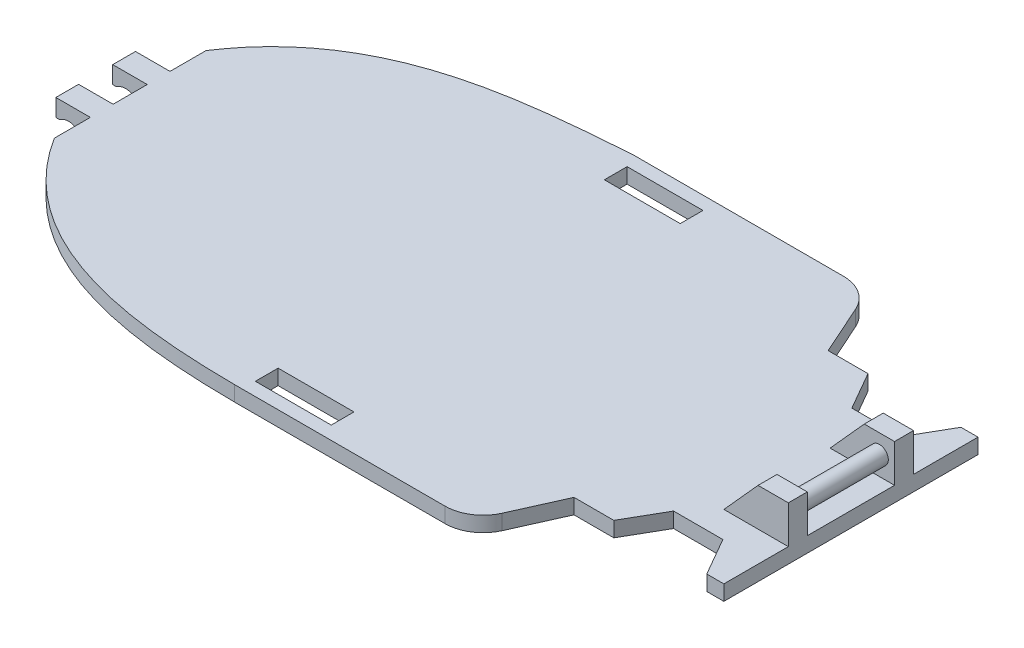
SolidWorks part; units mm, degrees
ref_plane "Front Plane" through (0, 0, 0) normal (0, 0, 1) x (1, 0, 0)
ref_plane "Top Plane" through (0, 0, 0) normal (0, 1, 0) x (1, 0, 0)
ref_plane "Right Plane" through (0, 0, 0) normal (1, 0, 0) x (0, 0, -1)
sketch "Sketch1" plane through (0, 0, 0) normal (0, 1, 0) x (1, 0, 0)
  line L0 (-110, 0) -> (0, 0)
  line L1 (0, 0) -> (0, -105)
  line L2 (0, -105) -> (-110, -105)
  line L4 (-190, -72.5) -> (-190, -32.5)
  spline S0 degree 3 poles (-190, -32.5) (-171.7074, -4.6189) (-138.9899, -2.1787) (-110, 0) knots 0 0 0 0 1 1 1 1
  spline S1 degree 2 poles (-190.0397, -35.2371) (-187.6331, -30.2964) (-183.9056, -25.9107) (-180.479, -21.8792) (-175.9528, -18.3354) (-171.8462, -15.1201) (-166.8566, -12.3231) (-164.564, -11.0379) (-162.0905, -9.8442) (-159.6124, -8.6482) (-157.2765, -7.6915) knots 0 0 0 0.25 0.25 0.5 0.5 0.75 0.75 0.875 0.875 1 1 1 construction
  spline S2 degree 2 poles (-157.2765, -7.6915) (-155.8569, -7.11) (-154.4721, -6.6099) (-153.0466, -6.0951) (-151.6197, -5.6536) (-148.8172, -4.7863) (-145.7427, -4.1123) (-142.8487, -3.4777) (-139.6519, -3.0009) (-136.688, -2.5589) (-133.369, -2.2385) knots 0 0 0 0.125 0.125 0.25 0.25 0.5 0.5 0.75 0.75 1 1 1 construction
  spline S3 degree 3 poles (-190, -72.5) (-172.2628, -100.7004) (-139.266, -104.8361) (-110, -105) knots 0 0 0 0 1 1 1 1
  point P11 (-190, -52.5)
  point P12 (0, -52.5)
  dimension "D4" = 40
  dimension "D1" = 110
  dimension "D2" = 105
  dimension "D3" = 190
  dimension "D5" = 110
extrude "Boss-Extrude1" add sketch "Sketch1" along normal blind 4
sketch "Sketch2" plane through (0, 0, 105) normal (0, 0, 1) x (1, 0, 0)
  line L0 (-190, 4) -> (-201, 4)
  line L1 (-178, 0) -> (-191, -11)
  line L2 (57.75, 0) -> (-57.75, 0) construction
  line L3 (-191, -11) -> (-201, -11)
  line L6 (-190, 4) -> (-178, 0)
  line L7 (-201, 4) -> (-201, -11)
  dimension "D1" = 11
  dimension "D2" = 15
  dimension "D5" = 10
extrude "Boss-Extrude2" add sketch "Sketch2" along normal mid plane 6 from offset 45 offset against normal yes
ref_plane "Plane1" through (0, 0, 52.5) normal (0, 0, 1) x (1, 0, 0)
mirror "Mirror1" about plane through (0, 0, 52.5) normal (0, 0, 1) of "Boss-Extrude2"
ref_plane "Plane2" through (-100, 0, 0) normal (1, 0, 0) x (0, 0, -1)
sketch "Sketch5" plane through (0, 0, 105) normal (0, 0, 1) x (1, 0, 0)
  line L0 (-16.9798, 4) -> (-7.9798, 14)
  line L1 (-110, 4) -> (0, 4) construction
  line L2 (-7.9798, 14) -> (0, 14)
  line L3 (0, 14) -> (0, 4)
  line L4 (0, 4) -> (-16.9798, 4)
  dimension "D1" = 10
  dimension "D2" = 9
extrude "Boss-Extrude3" add sketch "Sketch5" along direction (0, 0, 1) on the side against the normal mid plane 6 from offset 39 contours L2 L3 L4 L0 offset against normal yes
mirror "Mirror4" about plane through (0, 0, 52.5) normal (0, 0, 1) of "Boss-Extrude3"
sketch "Sketch6" plane through (0, 0, 42) normal (0, 0, 1) x (1, 0, 0)
  line L0 (0, -2.2) -> (0, 2.2) construction
  line L1 (-110, 4) -> (0, 4) construction
  circle A0 centre (-4, 10) radius 2.5
  dimension "D1" = 5
  dimension "D2" = 4
  dimension "D3" = 6
extrude "Boss-Extrude4" add sketch "Sketch6" along normal up to body separate body
sketch "Sketch7" plane through (0, 4, 0) normal (0, 1, 0) x (1, 0, 0)
  line L0 (-110, -105) -> (0, -105) construction
  line L1 (-108, -101.5) -> (-88, -101.5)
  line L2 (-108, -101.5) -> (-108, -95.5)
  line L3 (-108, -95.5) -> (-88, -95.5)
  line L4 (-88, -101.5) -> (-88, -95.5)
  dimension "D1" = 2
  dimension "D2" = 20
  dimension "D3" = 6
  dimension "D4" = 3.5
extrude "Cut-Extrude1" cut sketch "Sketch7" against normal blind 10
mirror "Mirror5" about plane through (0, 0, 52.5) normal (0, 0, 1) of "Cut-Extrude1"
sketch "Sketch8" plane through (0, 4, 0) normal (0, 1, 0) x (1, 0, 0)
  line L0 (-13.75, -52.5) -> (13.75, -52.5) construction
  line L1 (-190, -48) -> (-190, -57) construction
  circle A0 centre (-150, -52.5) radius 7.5
  dimension "D2" = 15
  dimension "D1" = 40
sketch "Sketch9" plane through (0, 0, 52.5) normal (0, 0, 1) x (1, 0, 0)
  line L0 (-150, 4) -> (-163.8674, -3.4662)
  line L1 (-142.5, 4) -> (-157.5, 4) construction
sketch "Sketch10" plane through (0, 4, 0) normal (0, 1, 0) x (1, 0, 0)
  line L0 (0, -19) -> (-39.5, -19)
  line L1 (0, -2.2) -> (0, 2.2) construction
  line L2 (-39.5, -19) -> (-48, 0)
  line L3 (-2.2, 0) -> (2.2, 0) construction
  line L4 (-48, 0) -> (0, 0)
  line L5 (0, 0) -> (0, -19)
  dimension "D1" = 19
  dimension "D2" = 8.5
  dimension "D3" = 48
extrude "Cut-Extrude2" cut sketch "Sketch10" against normal through all both and the other way through all contours L2 L4 L5 L0
mirror "Mirror6" about plane through (0, 0, 52.5) normal (0, 0, 1) of "Cut-Extrude2"
fillet "Fillet1" radius 10 2 edges at (-48, 2, 0) (-48, 2, 105)
sketch "Sketch11" plane through (0, 4, 0) normal (0, 1, 0) x (1, 0, 0)
  line L0 (-4.5, -19) -> (-10.25, -29)
  line L1 (0, -19) -> (-39.5, -19) construction
  line L2 (-10.25, -29) -> (-23.25, -29)
  line L3 (-23.25, -29) -> (-29, -19)
  line L4 (-29, -19) -> (-4.5, -19)
  point P9 (-16.75, -19)
  point P10 (-16.75, -29)
  dimension "D2" = 10.5
  dimension "D3" = 10
  dimension "D4" = 13
extrude "Cut-Extrude3" cut sketch "Sketch11" against normal through all both and the other way through all
mirror "Mirror7" about plane through (0, 0, 52.5) normal (0, 0, 1) of "Cut-Extrude3"
sketch "Sketch12" plane through (0, 0, 0) normal (1, 0, 0) x (0, 0, -1)
  line L0 (-63, 14) -> (-64, 14) construction
  line L1 (-69, 14) -> (-63, 14) construction
  line L2 (-42, 14) -> (-41, 14) construction
  line L3 (-36, 14) -> (-42, 14) construction
  line L4 (-41, 14) -> (-41, 3.5219) construction
  line L5 (-42, 4) -> (-38.9627, 4) construction
  line L7 (-64, 14) -> (-41, 14)
  line L8 (-64, 14) -> (-64, 4)
  line L9 (-64, 4) -> (-41, 4)
  line L10 (-41, 14) -> (-41, 4)
extrude "Cut-Extrude6" cut sketch "Sketch12" against normal blind 21
sketch "Sketch13" plane through (0, 0, 64) normal (0, 0, -1) x (-1, 0, 0)
  line L0 (7.9798, 14) -> (7.9798, 4.2522) construction
  line L1 (0, 14) -> (7.9798, 4) construction
  line L2 (0, 13.75) -> (0, -13.75) construction
  line L3 (7.9798, 14) -> (0, 14) construction
  line L4 (0, 4) -> (4.5, 4) construction
  line L5 (0, 4) -> (7.9798, 14) construction
  circle A0 centre (3.9899, 9) radius 2.35
  dimension "D1" = 4.7
extrude "Boss-Extrude5" add sketch "Sketch13" along normal up to next
sketch "Sketch14" plane through (0, 0, 52.5) normal (0, 0, 1) x (1, 0, 0)
  line L0 (-201, 4) -> (-201, -11) construction
  line L1 (-201, 4) -> (-201, -11) construction
  line L2 (-190, 4) -> (-201, -11) construction
  line L4 (-201, 4) -> (-191, -11) construction
  line L5 (-198.0957, 4) -> (-198.0957, -0.5654)
  line L6 (-190, 4) -> (-201, 4) construction
  line L7 (-201, -11) -> (-191, -11) construction
  line L8 (-198.0957, -11) -> (-202.7192, -12.1152)
  line L9 (-202.7192, -12.1152) -> (-202.5885, 4.843)
  line L10 (-202.5885, 4.843) -> (-198.0957, 4)
  line L11 (-198.0957, -6.9618) -> (-198.0957, -11)
  arc A0 (-198.0957, -6.9618) -> (-198.0957, -0.5654) centre (-195.6933, -3.7636) ccw
extrude "Cut-Extrude7" cut sketch "Sketch14" against normal through all both and the other way through all
sketch "Sketch15" plane through (-198.0957, 0, 0) normal (-1, 0, 0) x (0, 0, 1)
  line L4 (63, 4) -> (57, 4)
  line L5 (57, 4) -> (57, -0.5654)
  line L6 (57, -0.5654) -> (63, -0.5654)
  line L7 (63, -0.5654) -> (63, 4)
  line L8 (63, 4) -> (57, 4)
  line L9 (57, 4) -> (57, -0.5654)
  line L10 (57, -0.5654) -> (63, -0.5654)
  line L11 (63, -0.5654) -> (63, 4)
  line L12 (42, -0.5654) -> (48, -0.5654)
  line L13 (48, -0.5654) -> (48, 4)
  line L14 (48, 4) -> (42, 4)
  line L15 (42, 4) -> (42, -0.5654)
  line L16 (42, -0.5654) -> (48, -0.5654)
  line L17 (48, -0.5654) -> (48, 4)
  line L18 (48, 4) -> (42, 4)
  line L19 (42, 4) -> (42, -0.5654)
  line L20 (42, -11) -> (48, -11)
  line L21 (48, -11) -> (48, -6.9618)
  line L22 (48, -6.9618) -> (42, -6.9618)
  line L23 (42, -6.9618) -> (42, -11)
  line L24 (42, -11) -> (48, -11)
  line L25 (48, -11) -> (48, -6.9618)
  line L26 (48, -6.9618) -> (42, -6.9618)
  line L27 (42, -6.9618) -> (42, -11)
  line L28 (63, -6.9618) -> (57, -6.9618)
  line L29 (57, -6.9618) -> (57, -11)
  line L30 (57, -11) -> (63, -11)
  line L31 (63, -11) -> (63, -6.9618)
  line L32 (63, -6.9618) -> (57, -6.9618)
  line L33 (57, -6.9618) -> (57, -11)
  line L34 (57, -11) -> (63, -11)
  line L35 (63, -11) -> (63, -6.9618)
  dimension "D1" = 0
  dimension "D2" = 0
  dimension "D3" = 0
  dimension "D4" = 0
extrude "Boss-Extrude6" add sketch "Sketch15" along normal blind 1
